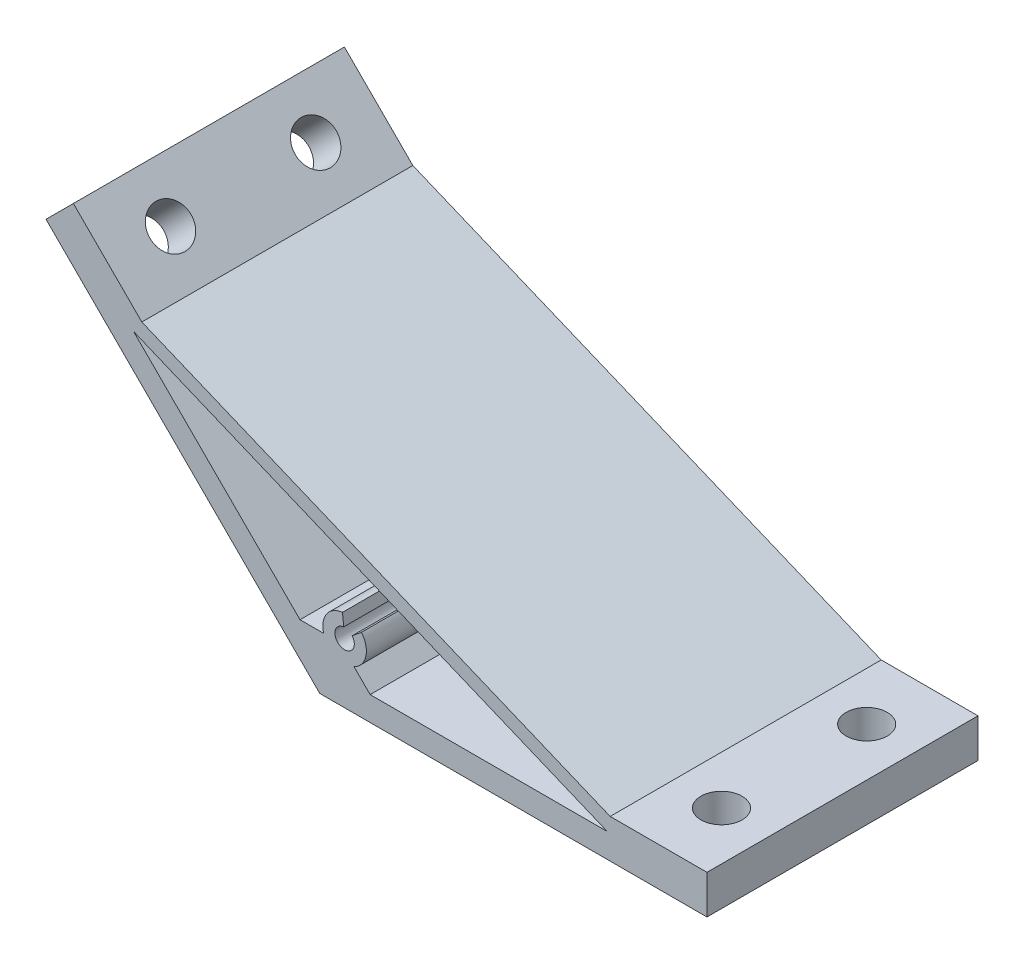
SolidWorks part; units mm, degrees
ref_plane "前视基准面" through (0, 0, 0) normal (0, 0, 1) x (1, 0, 0)
ref_plane "上视基准面" through (0, 0, 0) normal (0, 1, 0) x (1, 0, 0)
ref_plane "右视基准面" through (0, 0, 0) normal (1, 0, 0) x (0, 0, -1)
sketch "草图1" plane through (0, 0, 0) normal (0, 0, 1) x (1, 0, 0)
  line L0 (6992.6877, -1288.6549) -> (7072.6877, -1288.6549)
  line L1 (7003.0909, -1283.6549) -> (7052.0909, -1283.6549)
  line L2 (7052.6877, -1280.6549) -> (7072.6877, -1280.6549)
  line L3 (7003.0909, -1283.6549) -> (7029.4034, -1283.6549)
  line L4 (7072.6877, -1288.6549) -> (7072.6877, -1280.6549)
  line L5 (6997.6265, -1274.2736) -> (6997.3838, -1271.7854)
  line L6 (6999.3656, -1274.9939) -> (7001.2967, -1273.4062)
  line L7 (6992.6877, -1288.6549) -> (6936.1191, -1232.0864)
  line L8 (6988.6024, -1277.4986) -> (6954.2187, -1243.1149)
  line L9 (6955.9181, -1240.5717) -> (6941.776, -1226.4295)
  line L10 (6936.1191, -1232.0864) -> (6941.776, -1226.4295)
  line L11 (6955.9181, -1240.5717) -> (7052.6877, -1280.6549)
  line L12 (6954.2187, -1243.1149) -> (7052.0909, -1283.6549)
  line L13 (7052.0909, -1283.6549) -> (7009.0909, -1283.6549)
  line L14 (7003.0909, -1283.6549) -> (6999.7605, -1280.3246)
  line L15 (6988.6024, -1277.4986) -> (6993.4934, -1277.4986)
  arc A0 (6997.3838, -1271.7854) -> (6993.4934, -1277.4986) centre (6997.8207, -1276.2641) ccw
  arc A1 (6999.7605, -1280.3246) -> (7001.2967, -1273.4062) centre (6997.8207, -1276.2641) ccw
  arc A2 (6997.6265, -1274.2736) -> (6999.3656, -1274.9939) centre (6997.8207, -1276.2641) ccw
extrude "凸台-拉伸1" add sketch "草图1" along normal mid plane 56 contours L11 L9 L10 L7 L0 L4 L2 A2 L5 A0 L15 L8 L12 L1 L3 L14 A1 L6
hole_wizard "Ø8.5 (8.5) 直径孔1" positions "草图3" profile "草图2" hole size "Ø8.5" standard "GB" end condition through all
sketch "草图3" plane through (2852.0164, 2852.0164, 0) normal (-0.7071, -0.7071, 0) x (0.7071, -0.7071, 0)
  line L1 (5775.7935, 28) -> (5775.7935, -28) construction
  line L2 (5795.7935, -28) -> (5775.7935, -28) construction
  point P1 (5785.7935, -15)
  point P18 (5785.7935, 15)
  dimension "D1" = 10
  dimension "D2" = 13
  dimension "D3" = 2
sketch "草图2" plane through (6943.1902, -1239.1575, -15) normal (0, 0, 1) x (0.7071, -0.7071, 0)
  line L0 (0, 0) -> (0, 62.2254)
  line L1 (0, 62.2254) -> (4.25, 62.2254)
  line L2 (4.25, 62.2254) -> (4.25, 0)
  line L5 (4.25, 0) -> (0, 0)
  line L11 (0, -6.35) -> (0, 107.95) construction
  dimension "通孔孔直径" = 8.5
  dimension "通孔孔深度" = 62.2254
sketch "草图4" plane through (580.0623, 1400.3943, 0) normal (0.3827, 0.9239, 0) x (0.9239, -0.3827, 0)
  line L0 (6953.5479, -28) -> (6953.5479, 28) construction
  line L1 (6901.1766, -28) -> (7005.9192, -28) construction
  line L2 (6901.1766, 28) -> (7005.9192, 28) construction
ref_plane "基准面1" through (6424.2406, -2661.0076, 0) normal (-0.9239, 0.3827, 0) x (0, 0, 1)
mirror "镜向1" about plane through (6424.2406, -2661.0076, 0) normal (-0.9239, 0.3827, 0) of "Ø8.5 (8.5) 直径孔1"
